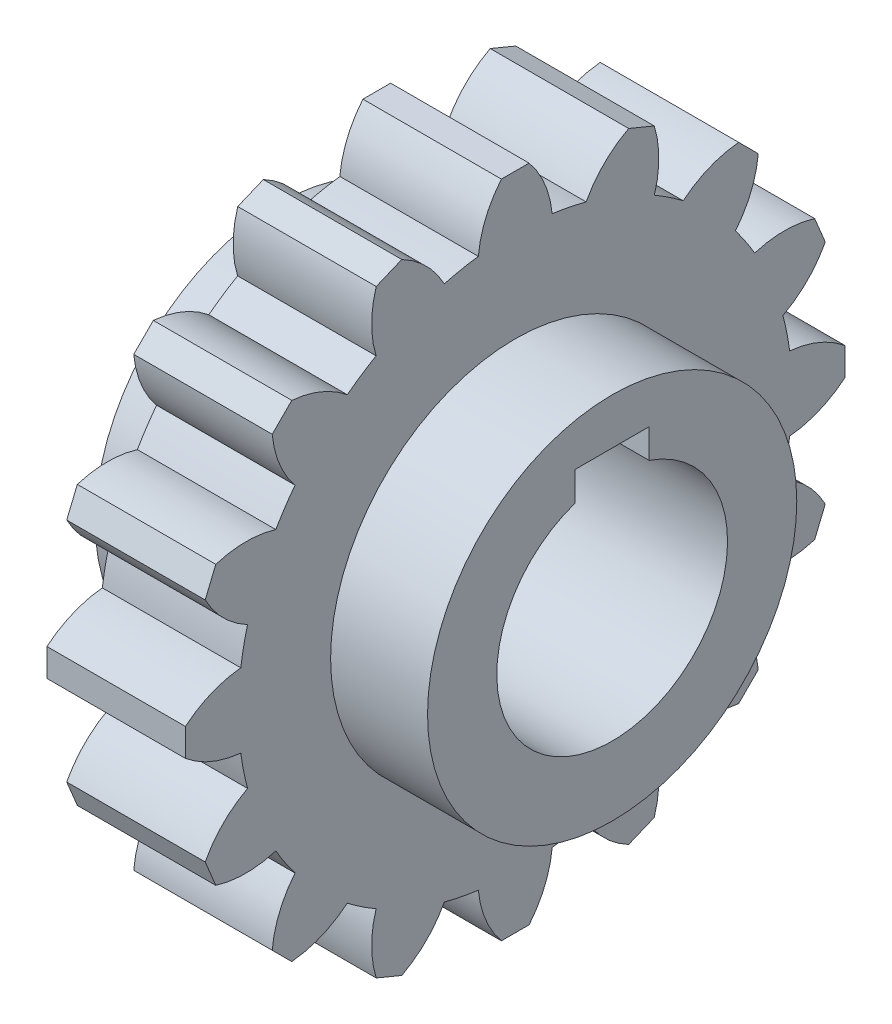
SolidWorks part; units mm, degrees
ref_plane "Front Plane" through (0, 0, 0) normal (0, 0, 1) x (1, 0, 0)
ref_plane "Top Plane" through (0, 0, 0) normal (0, 1, 0) x (1, 0, 0)
ref_plane "Right Plane" through (0, 0, 0) normal (1, 0, 0) x (0, 0, -1)
sketch "Sketch1" plane through (0, 0, 0) normal (1, 0, 0) x (0, 0, -1)
  circle A0 centre (0, 0) radius 30
  dimension "D1" = 60
extrude "Boss-Extrude1" add sketch "Sketch1" along normal mid plane 15
sketch "Sketch2" plane through (7.5, 0, 0) normal (1, 0, 0) x (0, 0, -1)
  line L0 (0, 0) -> (0, 36.9015) construction
  line L1 (-1.5, 35.7321) -> (1.5, 35.7321)
  arc A0 (4, 29.7321) -> (-4, 29.7321) centre (0, 0) ccw
  circle A1 centre (0, 0) radius 30 construction
  arc A2 (-1.5, 35.7321) -> (-4, 29.7321) centre (6.9505, 28.6902) ccw
  arc A4 (1.5, 35.7321) -> (4, 29.7321) centre (-6.9505, 28.6902) cw
  dimension "D5" = 11
  dimension "D6" = 11
  dimension "D3" = 4
  dimension "D4" = 6
extrude "Boss-Extrude2" add sketch "Sketch2" against normal up to surface (15 mm away) up to face at (-7.5, 0, -30)
pattern_circular "CirPattern1" count 16 over 360 about axis through (0, 0, 0) along (1, 0, 0) of "Boss-Extrude2"
sketch "Sketch4" plane through (0, 0, 0) normal (1, 0, 0) x (0, 0, -1)
  circle A0 centre (0, 0) radius 20
  dimension "D1" = 40
extrude "Boss-Extrude3" add sketch "Sketch4" along normal mid plane 36
sketch "Sketch5" plane through (18, 0, 0) normal (1, 0, 0) x (0, 0, -1)
  line L0 (0, 0) -> (0, 15) construction
  line L1 (-4, 15) -> (4, 15)
  line L2 (-4, 15) -> (-4, 11.8427)
  line L3 (4, 15) -> (4, 11.8427)
  arc A0 (-4, 11.8427) -> (4, 11.8427) centre (0, 0) ccw
  dimension "D1" = 25
  dimension "D2" = 15
  dimension "D3" = 8
extrude "Cut-Extrude1" cut sketch "Sketch5" against normal through all
